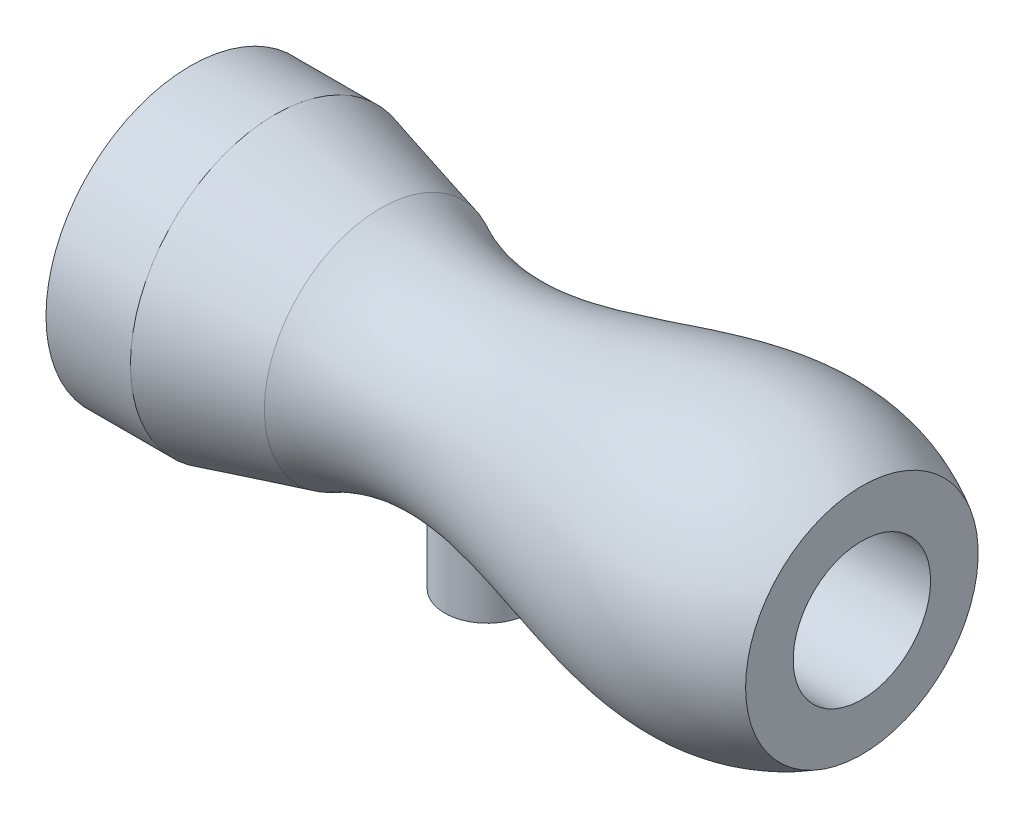
SolidWorks part; units mm, degrees
ref_plane "前基準面" through (0, 0, 0) normal (0, 0, 1) x (1, 0, 0)
ref_plane "上基準面" through (0, 0, 0) normal (0, 1, 0) x (1, 0, 0)
ref_plane "右基準面" through (0, 0, 0) normal (1, 0, 0) x (0, 0, -1)
sketch "草圖1" plane through (0, 0, 0) normal (0, 0, 1) x (1, 0, 0)
  line L0 (0, 0) -> (0, 72.265)
  line L1 (0, 72.265) -> (15.231, 72.265)
  line L2 (15.231, 72.265) -> (68.1078, 58.1645)
  line L3 (0, 0) -> (308.8232, 0)
  line L4 (308.8232, 0) -> (308.8232, 58.1645)
  spline S0 degree 3 poles (68.1078, 58.1645) (147.6604, 17.8156) (226.4198, 105.2917) (308.8232, 58.1645) knots 0 0 0 0 1 1 1 1
revolve "旋轉1" add sketch "草圖1" angle 360 about L3
sketch "草圖2" plane through (308.8232, 0, 0) normal (1, 0, 0) x (0, 0, -1)
  circle A0 centre (0, 0) radius 34.3708
extrude "除料-伸長1" cut sketch "草圖2" against normal blind 230
ref_plane "平面1" through (0, -70, 0) normal (0, 1, 0) x (1, 0, 0)
sketch "草圖3" plane through (0, -70, 0) normal (0, 1, 0) x (1, 0, 0)
  circle A0 centre (121.4013, 0) radius 11.25
  dimension "D1" = 22.5
extrude "伸長-薄件1" add sketch "草圖3" against normal blind 10 and the other way blind 33 thin
sketch "草圖4" plane through (0, 0, 0) normal (-1, 0, 0) x (0, 0, 1)
  circle A0 centre (0, 0) radius 72.265
extrude "填料-伸長1" add sketch "草圖4" along normal blind 27
